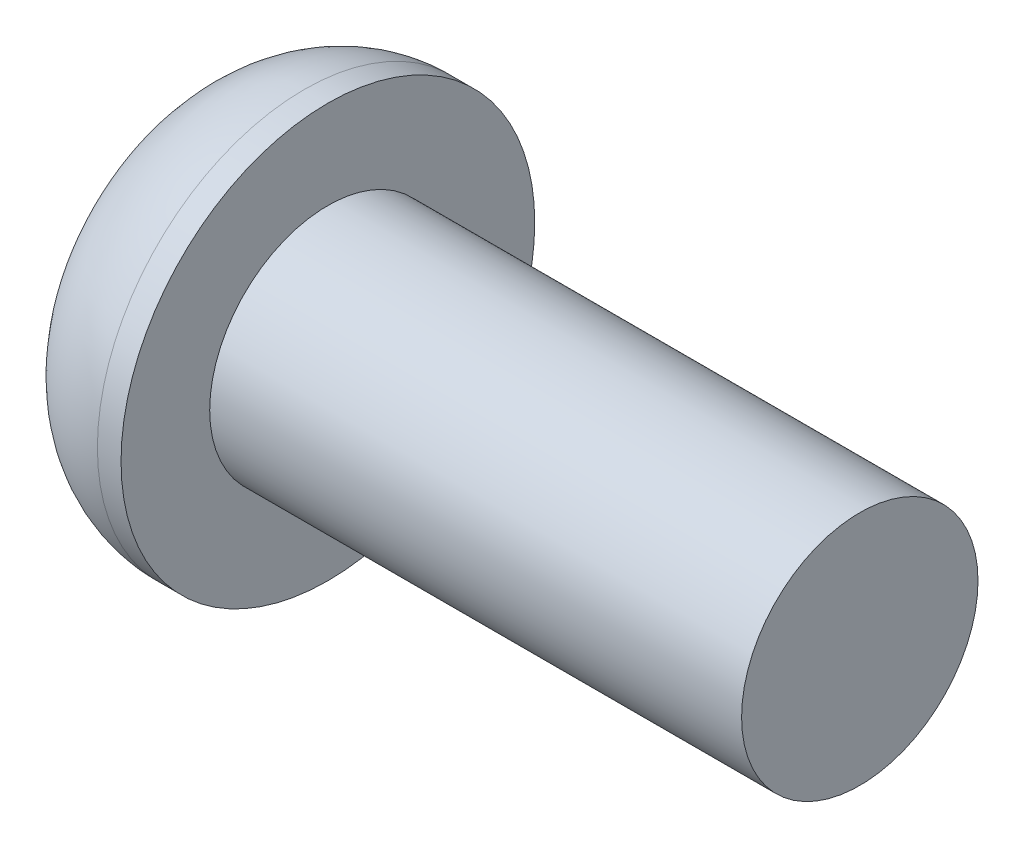
SolidWorks part; units mm, degrees
ref_plane "Front Plane" through (0, 0, 0) normal (0, 0, 1) x (1, 0, 0)
ref_plane "Top Plane" through (0, 0, 0) normal (0, 1, 0) x (1, 0, 0)
ref_plane "Right Plane" through (0, 0, 0) normal (1, 0, 0) x (0, 0, -1)
sketch "Sketch1" plane through (0, 0, 0) normal (0, 0, 1) x (1, 0, 0)
  line L0 (0, 0) -> (0, 2.8)
  line L1 (4.2, 7) -> (5, 7)
  line L2 (5, 7) -> (5, 4)
  line L3 (5, 4) -> (23, 4)
  line L4 (23, 4) -> (23, 0)
  line L5 (23, 0) -> (0, 0)
  line L6 (0, 0) -> (-9179.3886, 0) construction
  arc A0 (0, 2.8) -> (4.2, 7) centre (4.2, 2.8) cw
  dimension "D3" = 0.8
  dimension "D1" = 14
  dimension "D2" = 5
  dimension "D4" = 8
  dimension "D5" = 18
revolve "Revolve1" add sketch "Sketch1" angle 360 about L6
sketch "Sketch2" plane through (0, 0, 0) normal (-1, 0, 0) x (0, 0, 1)
  line L1 (2.8868, 0) -> (1.4434, 2.5)
  line L2 (1.4434, 2.5) -> (-1.4434, 2.5)
  line L3 (-1.4434, 2.5) -> (-2.8868, 0)
  line L4 (-2.8868, 0) -> (-1.4434, -2.5)
  line L5 (-1.4434, -2.5) -> (1.4434, -2.5)
  line L6 (1.4434, -2.5) -> (2.8868, 0)
  circle A0 centre (0, 0) radius 2.5 construction
  dimension "D1" = 5
extrude "Cut-Extrude1" cut sketch "Sketch2" against normal blind 4.2
